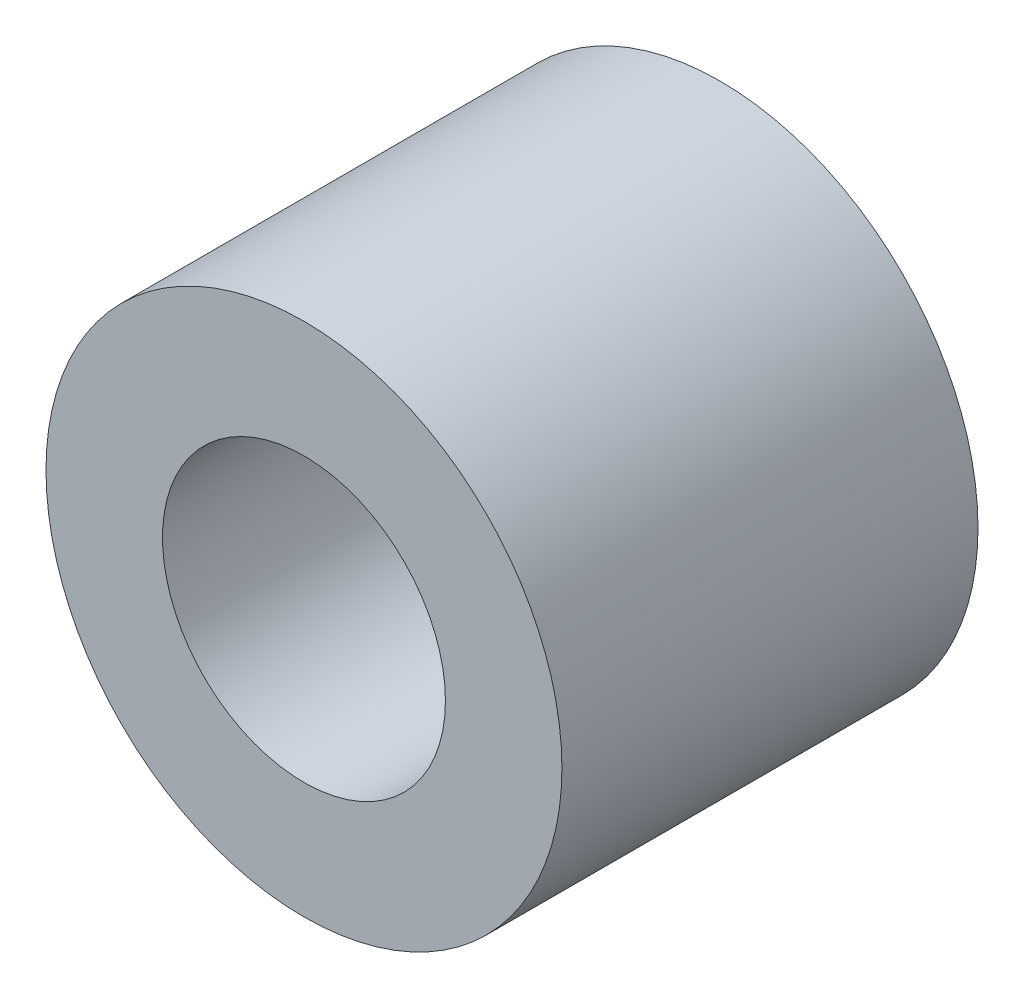
SolidWorks part; units mm, degrees
ref_plane "Front Plane" through (0, 0, 0) normal (0, 0, 1) x (1, 0, 0)
ref_plane "Top Plane" through (0, 0, 0) normal (0, 1, 0) x (1, 0, 0)
ref_plane "Right Plane" through (0, 0, 0) normal (1, 0, 0) x (0, 0, -1)
sketch "Sketch1" plane through (0, 0, 0) normal (0, 0, 1) x (1, 0, 0)
  circle A0 centre (0, 0) radius 3.1
  circle A1 centre (0, 0) radius 1.7
extrude "Boss-Extrude1" add sketch "Sketch1" along normal blind 5
